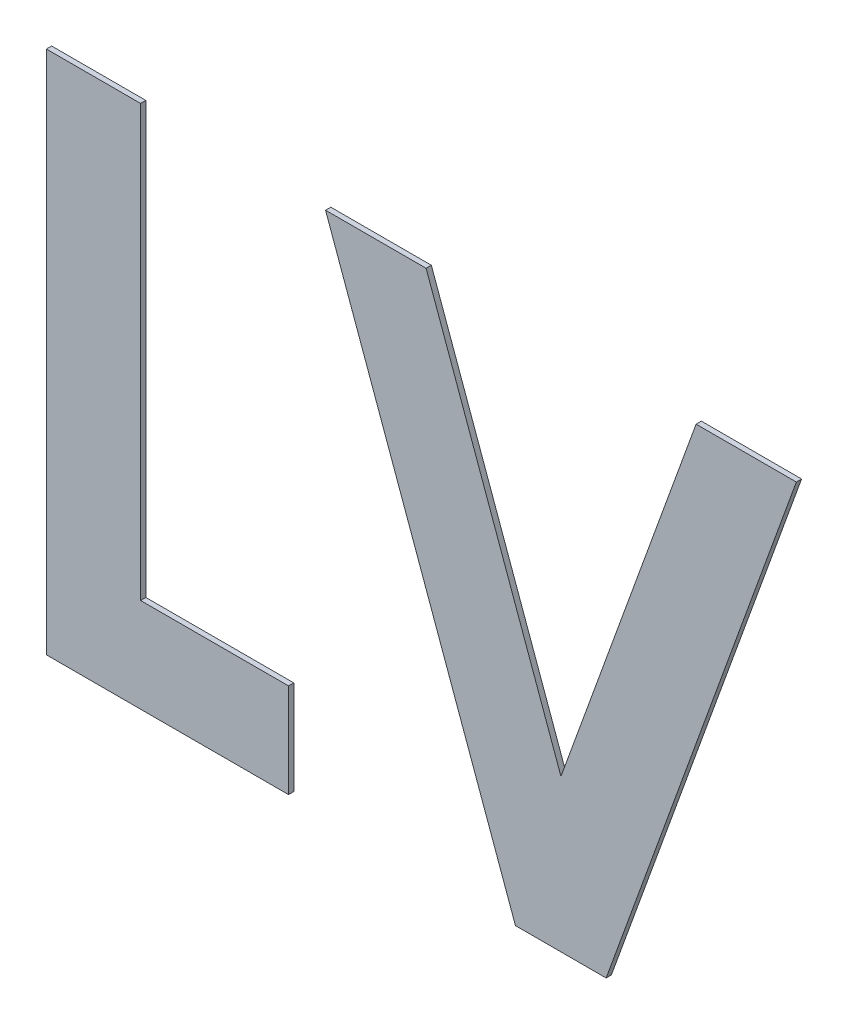
SolidWorks part; units mm, degrees
ref_plane "Front Plane" through (0, 0, 0) normal (0, 0, 1) x (1, 0, 0)
ref_plane "Top Plane" through (0, 0, 0) normal (0, 1, 0) x (1, 0, 0)
ref_plane "Right Plane" through (0, 0, 0) normal (1, 0, 0) x (0, 0, -1)
sketch "Sketch1" plane through (0, 0, 0) normal (0, 0, 1) x (1, 0, 0)
  line L0 (-12.5, 0) -> (12.5, 0)
  line L1 (-6.7949, 10) -> (-5, 10)
  line L2 (-5, 10) -> (-5, 1.7949)
  line L3 (-5, 1.7949) -> (-2.1795, 1.7949)
  line L4 (-2.1795, 1.7949) -> (-2.1795, 0)
  line L5 (-2.1795, 0) -> (-6.7949, 0)
  line L6 (-6.7949, 0) -> (-6.7949, 10)
  line L7 (-1.4744, 10) -> (0.4427, 10)
  line L8 (0.4427, 10) -> (3.0128, 2.8966)
  line L9 (3.0128, 2.8966) -> (5.5889, 10)
  line L10 (5.5889, 10) -> (7.5, 10)
  line L11 (7.5, 10) -> (3.8742, 0)
  line L12 (3.8742, 0) -> (2.1454, 0)
  line L13 (2.1454, 0) -> (-1.4744, 10)
  dimension "D1" = 25
extrude "Boss-Extrude1" add sketch "Sketch1" along normal blind 0.1 contours L6 L0 L4 L3 L2 L1 | L13 L0 L11 L10 L9 L8 L7
